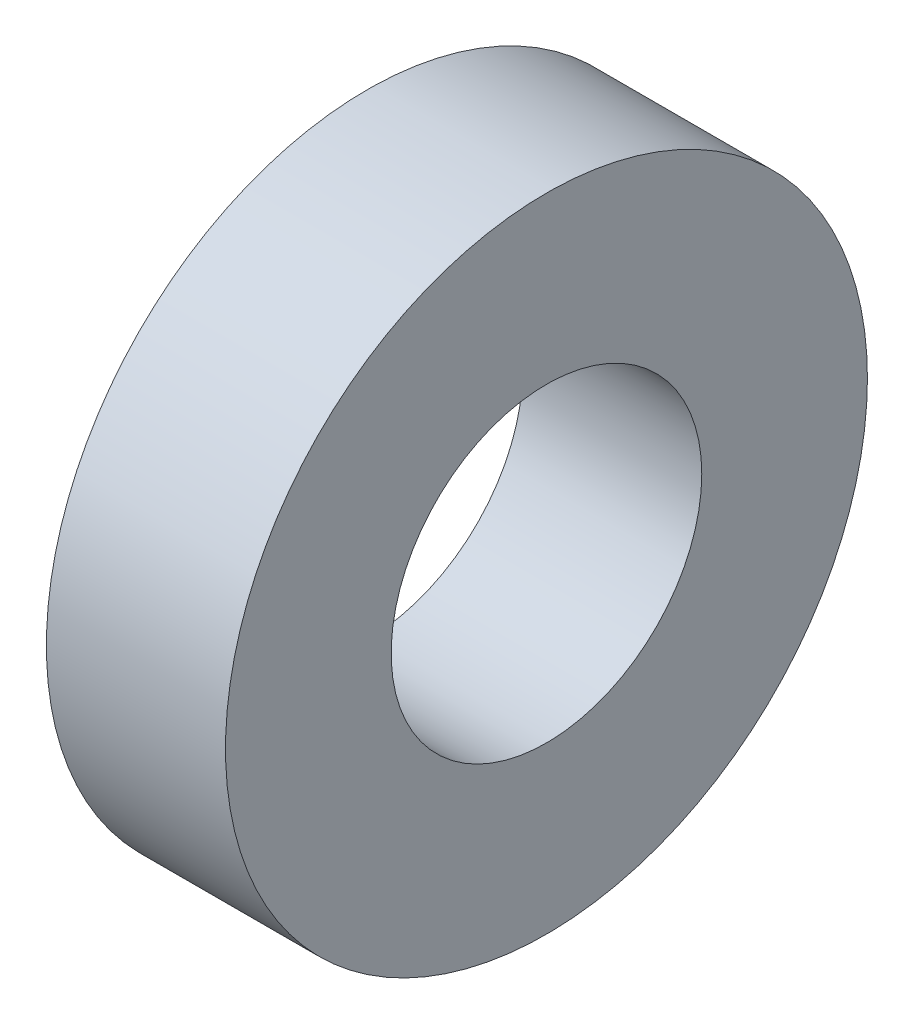
SolidWorks part; units mm, degrees
ref_plane "前视基准面" through (0, 0, 0) normal (0, 0, 1) x (1, 0, 0)
ref_plane "上视基准面" through (0, 0, 0) normal (0, 1, 0) x (1, 0, 0)
ref_plane "右视基准面" through (0, 0, 0) normal (1, 0, 0) x (0, 0, -1)
sketch "草图1" plane through (0, 0, 0) normal (1, 0, 0) x (0, 0, -1)
  circle A0 centre (0, 0) radius 15
  circle A1 centre (0, 0) radius 31
extrude "凸台-拉伸1" add sketch "草图1" along normal blind 17.3
